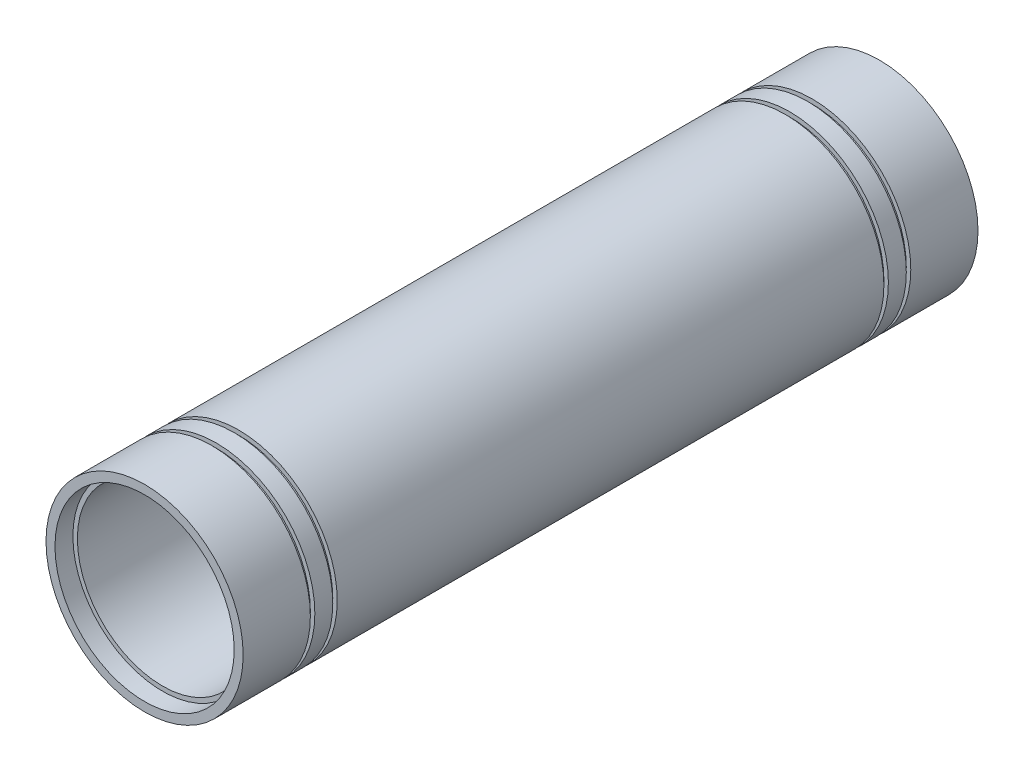
SolidWorks part; units mm, degrees
ref_plane "Спереди" through (0, 0, 0) normal (0, 0, 1) x (1, 0, 0)
ref_plane "Сверху" through (0, 0, 0) normal (0, 1, 0) x (1, 0, 0)
ref_plane "Справа" through (0, 0, 0) normal (1, 0, 0) x (0, 0, -1)
sketch "Эскиз1" plane through (0, 0, 0) normal (0, 0, 1) x (1, 0, 0)
  circle A0 centre (0, 0) radius 9.5
  circle A1 centre (0, 0) radius 11
  dimension "D1" = 19
  dimension "D2" = 22
extrude "Бобышка-Вытянуть1" add sketch "Эскиз1" along normal blind 82
sketch "Эскиз4" plane through (0, 0, 0) normal (0, 0, -1) x (-1, 0, 0)
  circle A0 centre (0, 0) radius 10
extrude "Вырез-Вытянуть2" cut sketch "Эскиз4" against normal blind 2
sketch "Эскиз5" plane through (0, 0, 82) normal (0, 0, 1) x (1, 0, 0)
  circle A0 centre (0, 0) radius 10
extrude "Вырез-Вытянуть3" cut sketch "Эскиз5" against normal blind 2
ref_plane "Плоскость1" through (0, 0, 74.5) normal (0, 0, 1) x (1, 0, 0)
sketch "Эскиз6" plane through (0, 0, 74.5) normal (0, 0, 1) x (1, 0, 0)
  circle A0 centre (0, 0) radius 10.5
  circle A2 centre (0, 0) radius 11.5
  dimension "D1" = 23
extrude "Вырез-Вытянуть4" cut sketch "Эскиз6" against normal blind 0.5
ref_plane "Плоскость2" through (0, 0, 72) normal (0, 0, 1) x (1, 0, 0)
sketch "Эскиз7" plane through (0, 0, 72) normal (0, 0, 1) x (1, 0, 0)
  circle A2 centre (0, 0) radius 11.5
  circle A4 centre (0, 0) radius 10.5
extrude "Вырез-Вытянуть5" cut sketch "Эскиз7" against normal blind 0.5
ref_plane "Плоскость3" through (0, 0, 41) normal (0, 0, 1) x (1, 0, 0)
mirror "Зеркальное отражение1" about plane through (0, 0, 41) normal (0, 0, 1) of "Вырез-Вытянуть5", "Вырез-Вытянуть4"
